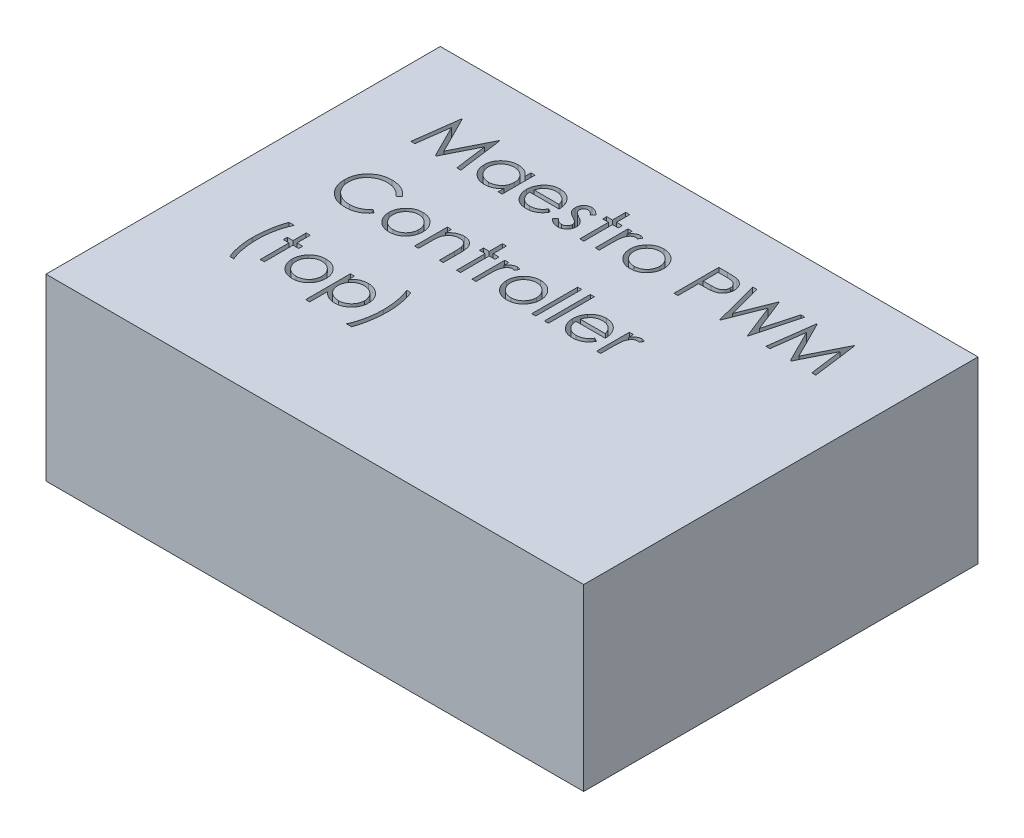
SolidWorks part; units mm, degrees
ref_plane "Front Plane" through (0, 0, 0) normal (0, 0, 1) x (1, 0, 0)
ref_plane "Top Plane" through (0, 0, 0) normal (0, 1, 0) x (1, 0, 0)
ref_plane "Right Plane" through (0, 0, 0) normal (1, 0, 0) x (0, 0, -1)
sketch "Sketch1" plane through (0, 0, 0) normal (0, 1, 0) x (1, 0, 0)
  line L1 (0, 0) -> (38.1, 0)
  line L2 (0, 0) -> (0, 27.94)
  line L3 (0, 27.94) -> (38.1, 27.94)
  line L4 (38.1, 0) -> (38.1, 27.94)
extrude "Boss-Extrude1" add sketch "Sketch1" along normal blind 12.7
sketch "Sketch2" plane through (0, 12.7, 0) normal (0, 1, 0) x (1, 0, 0)
  text T0 "Maestro PWM\r\nController\r\n(top)"
extrude "Cut-Extrude1" cut sketch "Sketch2" against normal blind 5.08
